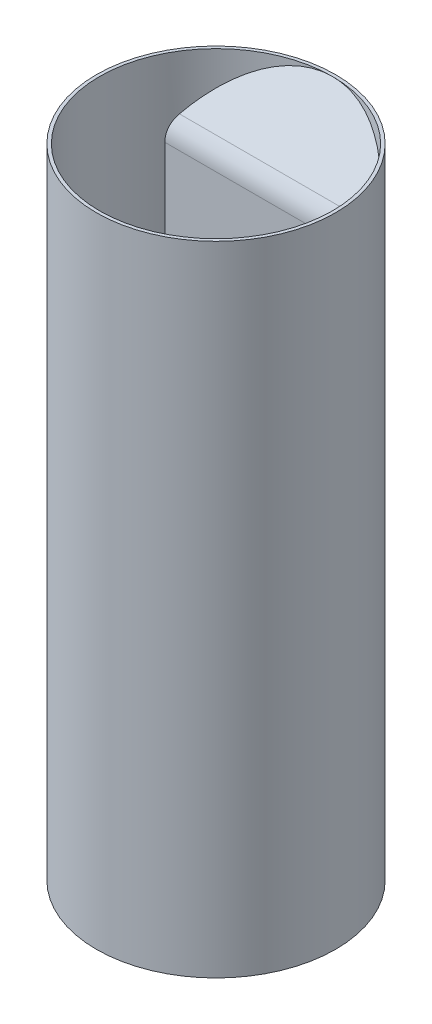
SolidWorks part; units mm, degrees
ref_plane "Piano frontale" through (0, 0, 0) normal (1, 0, 0) x (0, 1, 0)
ref_plane "Piano superiore" through (0, 0, 0) normal (0, 0, 1) x (0, 1, 0)
ref_plane "Piano destro" through (0, 0, 0) normal (0, 1, 0) x (-1, 0, 0)
sketch "Schizzo1" plane through (0, 0, 0) normal (0, 1, 0) x (-1, 0, 0)
  circle A0 centre (0, 0) radius 37.5
  dimension "D1" = 75
extrude "Estrusione-Estrusione1" add sketch "Schizzo1" along normal blind 200
sketch "Schizzo2" plane through (0, 200, 0) normal (0, 1, 0) x (-1, 0, 0)
  line L1 (-50, -56.5) -> (50, -56.5)
  line L2 (-50, -56.5) -> (-50, -16.5)
  line L3 (-50, -16.5) -> (50, -16.5)
  line L4 (50, -56.5) -> (50, -16.5)
  line L5 (-50, -56.5) -> (50, -16.5) construction
  line L6 (-50, -16.5) -> (50, -56.5) construction
  circle A0 centre (0, 0) radius 36.5
  point P3 (0, -36.5)
  dimension "D1" = 73
  dimension "D2" = 100
  dimension "D3" = 40
extrude "Taglio-Estrusione2" cut sketch "Schizzo2" against normal through all contours L3 A0
chamfer "Smusso3" distance 20 angle 45 2 edges at (0, 0, -16.5) (0, 200, -16.5)
fillet "Raccordo1" radius 10 2 edges at (0, 20, -16.5) (0, 180, -16.5)
